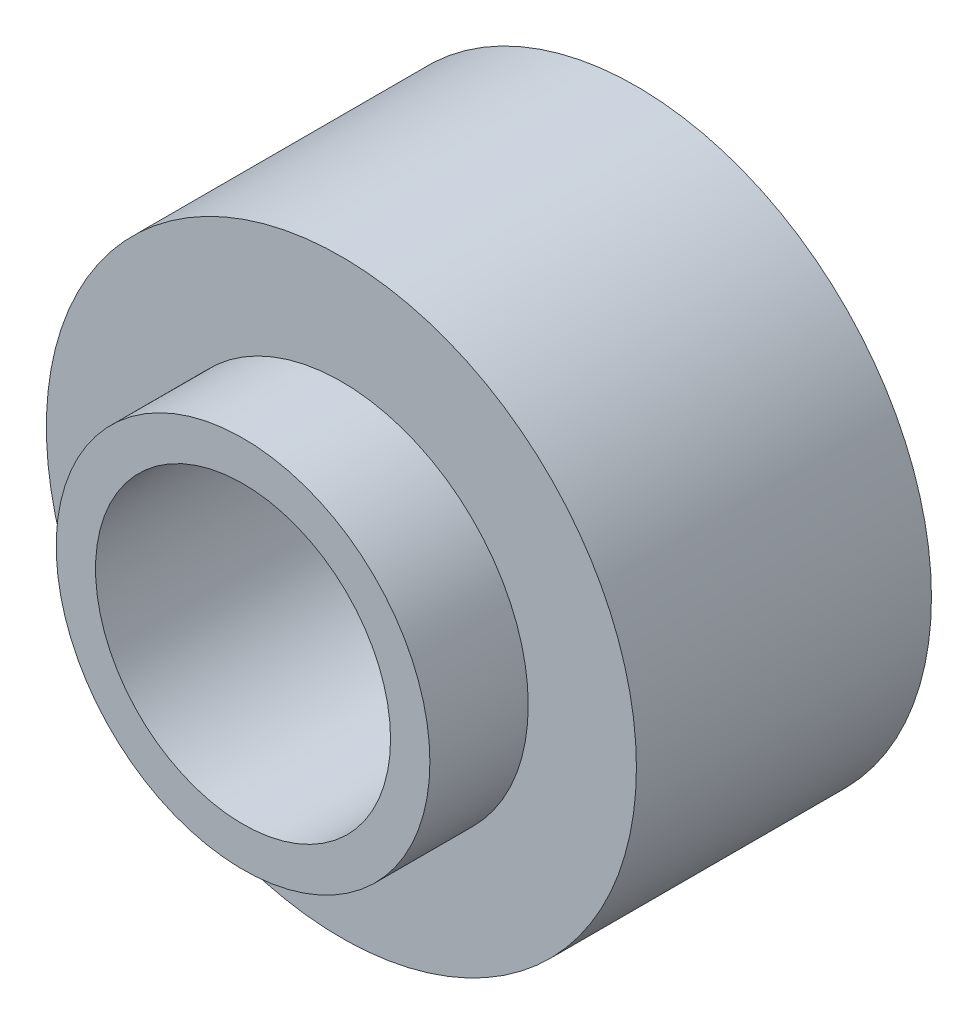
SolidWorks part; units mm, degrees
ref_plane "Front Plane" through (0, 0, 0) normal (0, 0, 1) x (1, 0, 0)
ref_plane "Top Plane" through (0, 0, 0) normal (0, 1, 0) x (1, 0, 0)
ref_plane "Right Plane" through (0, 0, 0) normal (1, 0, 0) x (0, 0, -1)
sketch "Sketch2" plane through (0, 0, 0) normal (0, 0, 1) x (1, 0, 0)
  circle A0 centre (0, 0) radius 0.375
  circle A1 centre (0, 0) radius 0.1875
  dimension "D1" = 0.75
  dimension "D2" = 0.375
extrude "Boss-Extrude1" add sketch "Sketch2" along normal blind 0.5
ref_plane "Plane1" through (0, 0, 0.5) normal (0, 0, 1) x (1, 0, 0)
sketch "Sketch3" plane through (0, 0, 0.5) normal (0, 0, 1) x (1, 0, 0)
  circle A2 centre (0, 0) radius 0.2375
  circle A3 centre (0, 0) radius 0.2375
  circle A4 centre (0, 0) radius 0.375
  circle A5 centre (0, 0) radius 0.375
  dimension "D1" = 0.05
  dimension "D2" = 0
extrude "Cut-Extrude1" cut sketch "Sketch3" against normal blind 0.125
